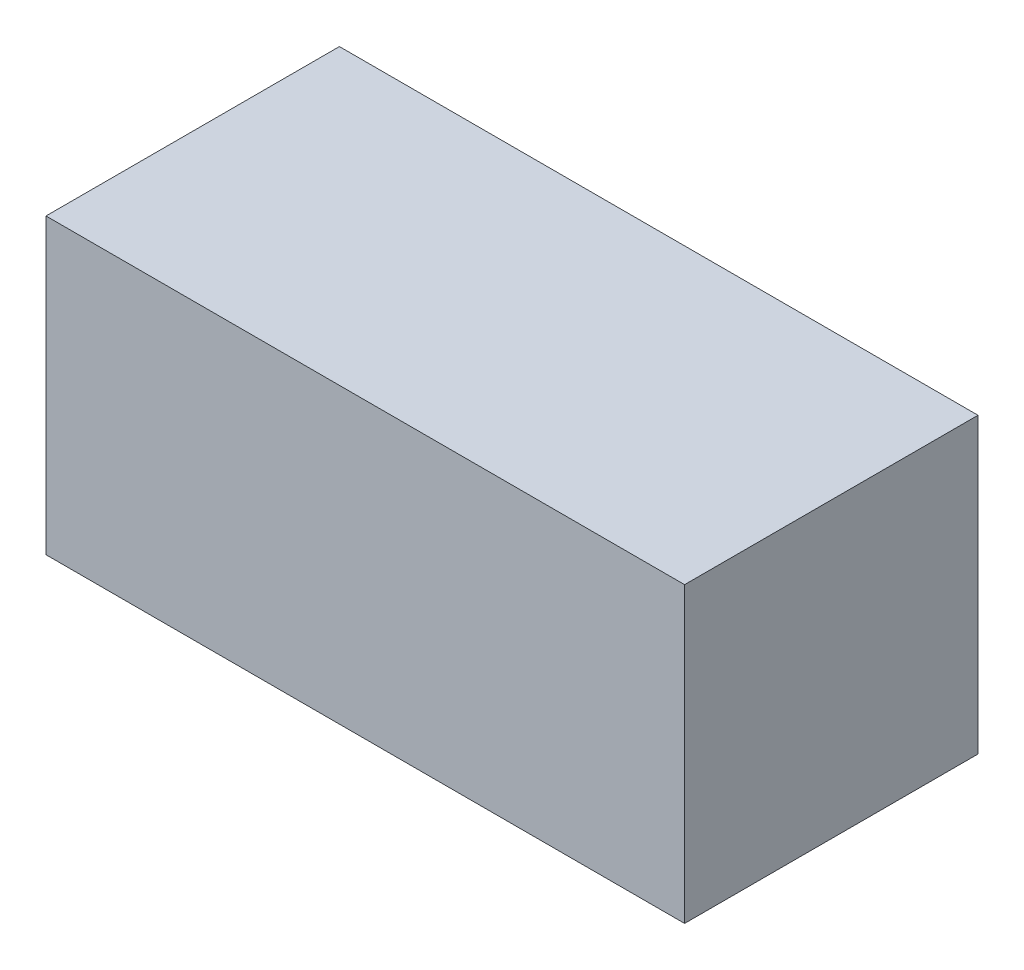
SolidWorks part; units mm, degrees
ref_plane "Front Plane" through (0, 0, 0) normal (0, 0, 1) x (1, 0, 0)
ref_plane "Top Plane" through (0, 0, 0) normal (0, 1, 0) x (1, 0, 0)
ref_plane "Right Plane" through (0, 0, 0) normal (1, 0, 0) x (0, 0, -1)
sketch "Sketch1" plane through (0, 0, 0) normal (0, 0, 1) x (1, 0, 0)
  line L0 (1.85, -0.85) -> (-1.85, -0.85)
  line L1 (-1.85, -0.85) -> (-1.85, 0.85)
  line L2 (-1.85, 0.85) -> (1.85, 0.85)
  line L3 (1.85, 0.85) -> (1.85, -0.85)
extrude "Component_Outline" add sketch "Sketch1" along normal blind 1.7 separate body
sketch3d "3DSketch1"
  line L0 (0, 0, 0) -> (1, 0, 0)
  line L1 (0, 0, 0) -> (0, 1, 0)
  line L2 (0, 0, 0) -> (0, 0, 1)
  point P0 (0, 0, 0)
